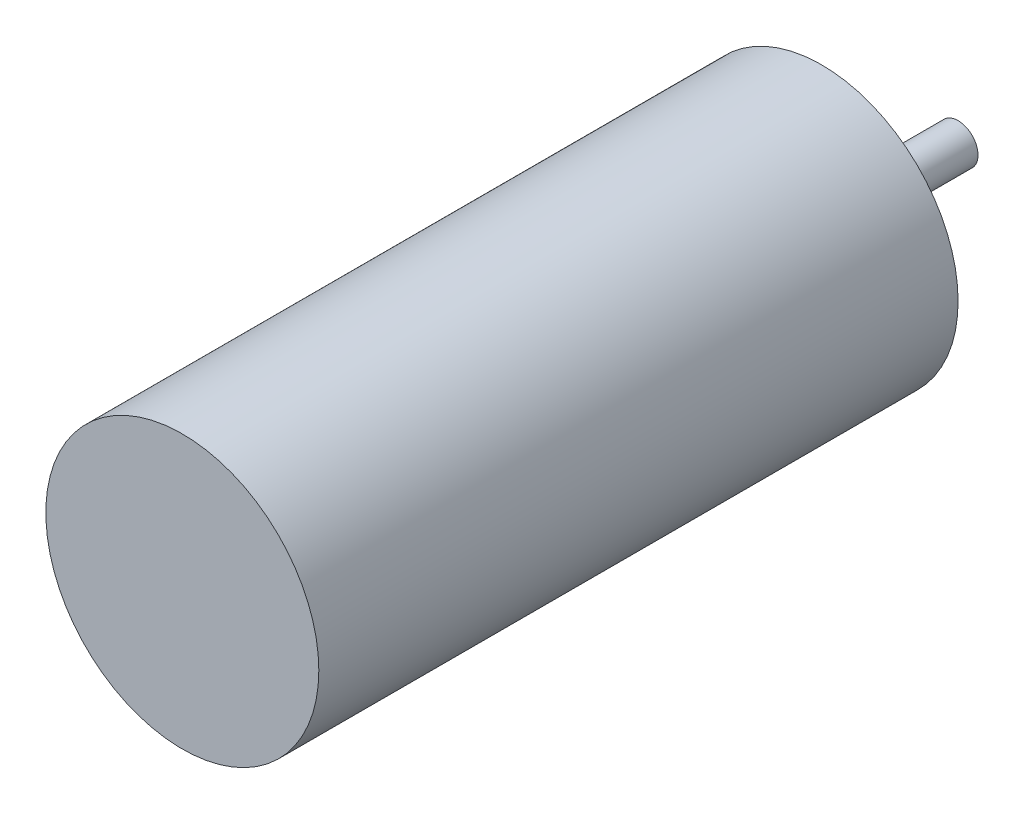
SolidWorks part; units mm, degrees
ref_plane "Front Plane" through (0, 0, 0) normal (0, 0, 1) x (1, 0, 0)
ref_plane "Top Plane" through (0, 0, 0) normal (0, 1, 0) x (1, 0, 0)
ref_plane "Right Plane" through (0, 0, 0) normal (1, 0, 0) x (0, 0, -1)
sketch "Sketch1" plane through (0, 0, 0) normal (0, 0, 1) x (1, 0, 0)
  circle A0 centre (0, 0) radius 12
  dimension "D1" = 24
extrude "Boss-Extrude1" add sketch "Sketch1" along normal blind 56.2
sketch "Sketch2" plane through (0, 0, 0) normal (0, 0, -1) x (-1, 0, 0)
  circle A0 centre (0, 0) radius 1.75
  dimension "D1" = 3.5
extrude "Boss-Extrude2" add sketch "Sketch2" along normal blind 12
